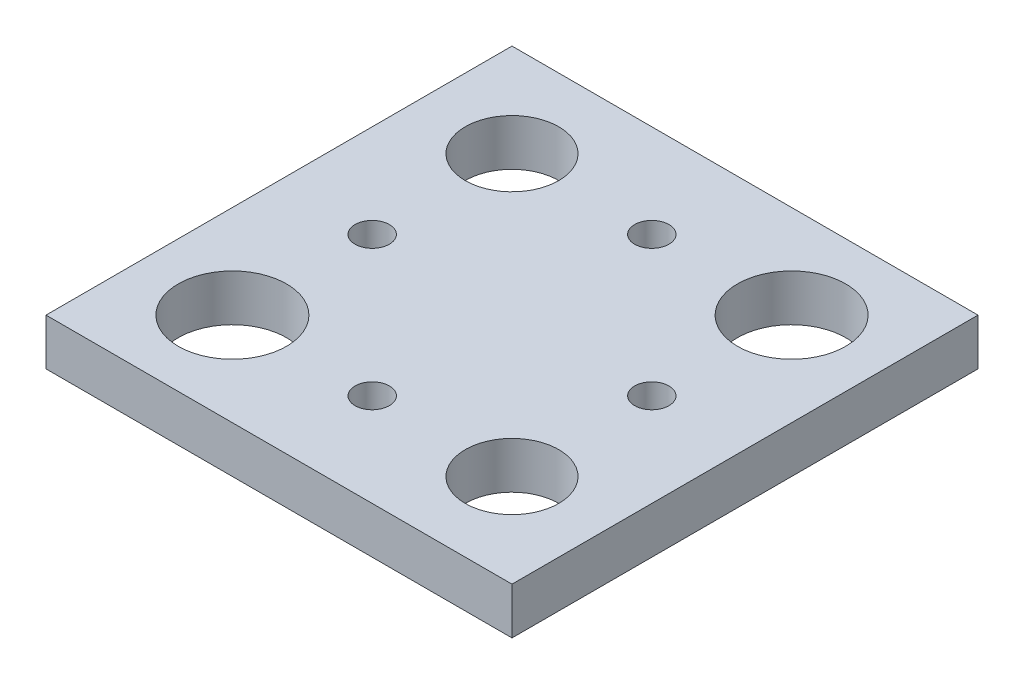
SolidWorks part; units mm, degrees
material "polylactic acid(PLA)(20%)"
ref_plane "Front Plane" through (0, 0, 0) normal (0, 0, 1) x (1, 0, 0)
ref_plane "Top Plane" through (0, 0, 0) normal (0, 1, 0) x (1, 0, 0)
ref_plane "Right Plane" through (0, 0, 0) normal (1, 0, 0) x (0, 0, -1)
sketch "Sketch1" plane through (0, 0, 0) normal (0, 1, 0) x (1, 0, 0)
  line L1 (-50, 50) -> (50, 50)
  line L2 (-50, 50) -> (-50, -50)
  line L3 (-50, -50) -> (50, -50)
  line L4 (50, 50) -> (50, -50)
  point P4 (50, 0)
  point P7 (0, -50)
  dimension "D1" = 100
extrude "Boss-Extrude1" add sketch "Sketch1" along normal blind 10
sketch "Sketch3" plane through (0, 0, 0) normal (0, 1, 0) x (1, 0, 0)
  circle A0 centre (-30, 30) radius 10.025
  circle A1 centre (30, 30) radius 10.025 construction
  circle A2 centre (30, -30) radius 10.025
  circle A3 centre (-30, -30) radius 10.025 construction
  circle A4 centre (-30, 30) radius 19.304 construction
  circle A5 centre (-30, -30) radius 19.304 construction
  circle A6 centre (30, 30) radius 19.304 construction
  circle A7 centre (0, 30) radius 3.675
  circle A8 centre (0, 30) radius 7.5 construction
  circle A9 centre (30, 0) radius 3.675
  circle A10 centre (0, -30) radius 3.675
  circle A11 centre (-30, 0) radius 3.675
  circle A14 centre (30, 30) radius 11.6125
  circle A15 centre (-30, -30) radius 11.6125
  point P3 (-30.696, 32.1759)
  point P4 (-29.7394, 29.7394)
  point P14 (0, 0)
  point P15 (-30, 30)
  point P16 (0, 0)
  point P22 (0, 0)
  point P29 (0, 0)
  dimension "D1" = 20.05
  dimension "D2" = 38.608
  dimension "D4" = 7.35
  dimension "D5" = 15
  dimension "D7" = 23.225
  dimension "D8" = 60
  dimension "D3" = 4
  dimension "D6" = 4
extrude "Cut-Extrude3" cut sketch "Sketch3" against normal through all and the other way through all
